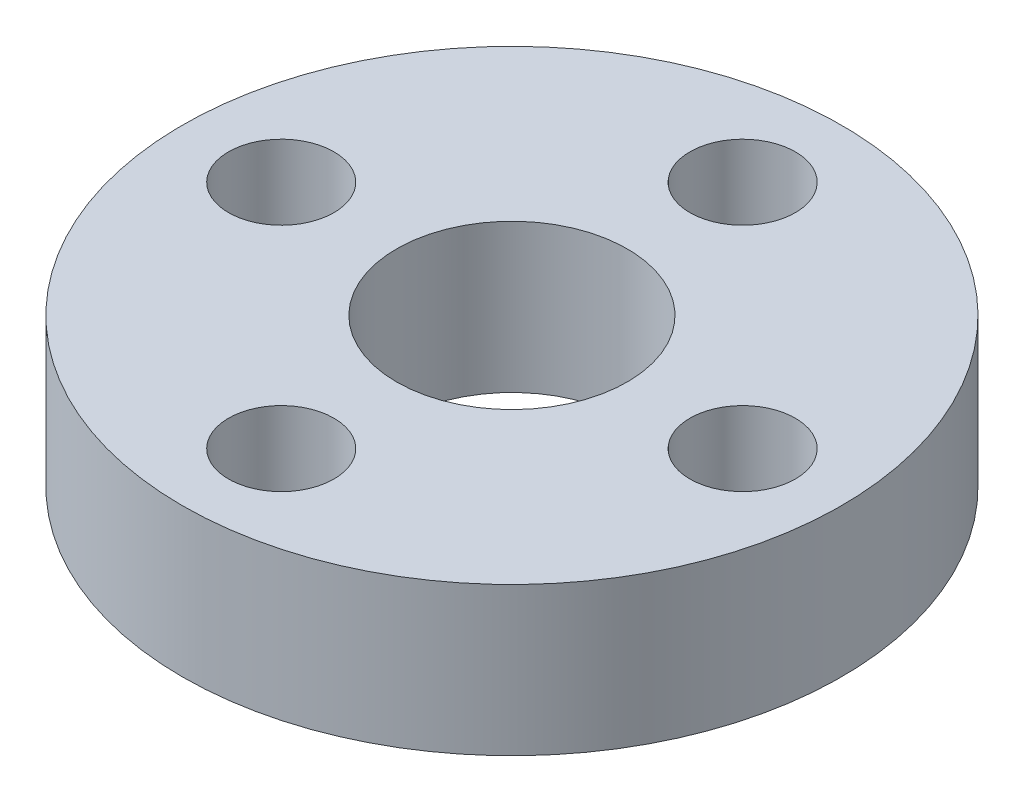
SolidWorks part; units mm, degrees
material "聚脂树脂"
ref_plane "前视基准面" through (0, 0, 0) normal (0, 0, 1) x (1, 0, 0)
ref_plane "上视基准面" through (0, 0, 0) normal (0, 1, 0) x (1, 0, 0)
ref_plane "右视基准面" through (0, 0, 0) normal (1, 0, 0) x (0, 0, -1)
other "Configuration Table"
sketch "草图1" plane through (0, 0, 0) normal (0, 1, 0) x (1, 0, 0)
  line L0 (0, 0) -> (0, 17.1458) construction
  line L1 (0, 0) -> (21.0507, 0) construction
  circle A0 centre (0, 0) radius 10
  circle A1 centre (0, 7) radius 1.6
  circle A2 centre (7, 0) radius 1.6
  circle A3 centre (0, 0) radius 3.5
  circle A4 centre (0, -7) radius 1.6
  circle A5 centre (-7, 0) radius 1.6
  dimension "D1" = 20
  dimension "D2" = 3.2
  dimension "D3" = 3.2
  dimension "D4" = 7
  dimension "D5" = 7
  dimension "D6" = 7
extrude "凸台-拉伸1" add sketch "草图1" along normal blind 4.5
